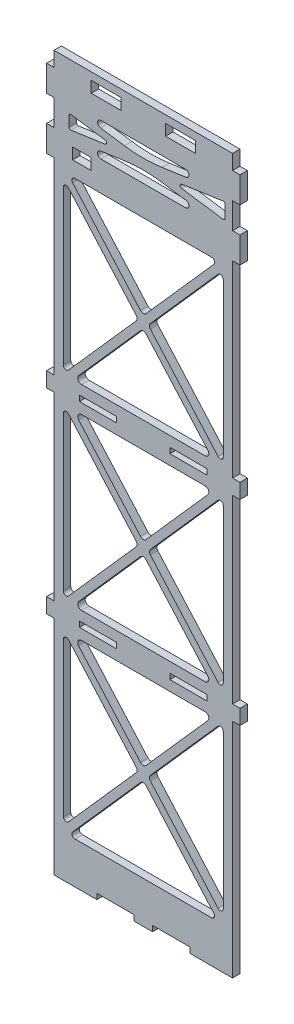
SolidWorks part; units mm, degrees
ref_plane "前视基准面" through (0, 0, 0) normal (0, 0, 1) x (1, 0, 0)
ref_plane "上视基准面" through (0, 0, 0) normal (0, 1, 0) x (1, 0, 0)
ref_plane "右视基准面" through (0, 0, 0) normal (1, 0, 0) x (0, 0, -1)
other "Configuration Table"
sketch "草图1" plane through (0, 0, 0) normal (0, 0, 1) x (1, 0, 0)
  line L0 (2550.9863, 1406.1084) -> (2502.9863, 1406.1084)
  line L1 (2500.9863, 1402.1084) -> (2500.9863, 1395.1084)
  line L2 (2500.9863, 1388.1084) -> (2500.9863, 1381.1084)
  line L3 (2500.9863, 1330.5084) -> (2500.9863, 1326.5084)
  line L4 (2500.9863, 1277.9084) -> (2500.9863, 1273.9084)
  line L5 (2550.9863, 1214.1084) -> (2539.4863, 1214.1084)
  line L6 (2529.4863, 1214.1084) -> (2524.4863, 1214.1084)
  line L7 (2514.4863, 1214.1084) -> (2502.9863, 1214.1084)
  line L8 (2552.9863, 1402.1084) -> (2552.9863, 1395.1084)
  line L9 (2552.9863, 1388.1084) -> (2552.9863, 1381.1084)
  line L10 (2502.9863, 1406.1084) -> (2502.9863, 1402.1084)
  line L11 (2502.9863, 1395.1084) -> (2502.9863, 1388.1084)
  line L12 (2500.9863, 1402.1084) -> (2502.9863, 1402.1084)
  line L13 (2500.9863, 1395.1084) -> (2502.9863, 1395.1084)
  line L14 (2500.9863, 1388.1084) -> (2502.9863, 1388.1084)
  line L15 (2500.9863, 1381.1084) -> (2502.9863, 1381.1084)
  line L16 (2500.9863, 1326.5084) -> (2502.9863, 1326.5084)
  line L17 (2502.9863, 1330.5084) -> (2500.9863, 1330.5084)
  line L18 (2502.9863, 1381.1084) -> (2502.9863, 1330.5084)
  line L19 (2500.9863, 1277.9084) -> (2502.9863, 1277.9084)
  line L20 (2502.9863, 1273.9084) -> (2500.9863, 1273.9084)
  line L21 (2502.9863, 1326.5084) -> (2502.9863, 1277.9084)
  line L22 (2502.9863, 1273.9084) -> (2502.9863, 1214.1084)
  line L23 (2550.9863, 1406.1084) -> (2550.9863, 1402.1084)
  line L24 (2550.9863, 1402.1084) -> (2552.9863, 1402.1084)
  line L25 (2552.9863, 1402.1084) -> (2552.9863, 1395.1084)
  line L26 (2552.9863, 1330.5084) -> (2552.9863, 1326.5084)
  line L27 (2552.9863, 1277.9084) -> (2552.9863, 1273.9084)
  line L28 (2550.9863, 1395.1084) -> (2550.9863, 1388.1084)
  line L29 (2552.9863, 1395.1084) -> (2550.9863, 1395.1084)
  line L30 (2552.9863, 1388.1084) -> (2550.9863, 1388.1084)
  line L31 (2552.9863, 1381.1084) -> (2550.9863, 1381.1084)
  line L32 (2552.9863, 1326.5084) -> (2550.9863, 1326.5084)
  line L33 (2550.9863, 1330.5084) -> (2552.9863, 1330.5084)
  line L34 (2550.9863, 1381.1084) -> (2550.9863, 1330.5084)
  line L35 (2552.9863, 1277.9084) -> (2550.9863, 1277.9084)
  line L36 (2550.9863, 1273.9084) -> (2552.9863, 1273.9084)
  line L37 (2550.9863, 1326.5084) -> (2550.9863, 1277.9084)
  line L38 (2550.9863, 1273.9084) -> (2550.9863, 1214.1084)
  line L39 (2508.5975, 1379.1084) -> (2526.9863, 1379.1084)
  line L40 (2507.9863, 1386.1084) -> (2512.9863, 1386.1084)
  line L41 (2507.9863, 1383.1084) -> (2512.9863, 1383.1084)
  line L42 (2545.375, 1379.1084) -> (2508.5975, 1379.1084)
  line L43 (2545.375, 1379.1084) -> (2538.8184, 1379.1084)
  line L44 (2515.1541, 1379.1084) -> (2508.5975, 1379.1084)
  line L45 (2508.8854, 1373.7575) -> (2525.0647, 1355.4711)
  line L46 (2527.7352, 1352.4528) -> (2544.3528, 1333.6711)
  line L47 (2507.9983, 1377.7783) -> (2523.2416, 1360.5499)
  line L48 (2528.9078, 1354.1458) -> (2545.0871, 1335.8594)
  line L49 (2545.0871, 1373.7575) -> (2528.9078, 1355.4711)
  line L50 (2526.2373, 1352.4528) -> (2509.6197, 1333.6711)
  line L51 (2545.9742, 1377.7783) -> (2530.7309, 1360.5499)
  line L52 (2525.0647, 1354.1458) -> (2508.8854, 1335.8594)
  line L53 (2523.2416, 1360.5499) -> (2524.0871, 1359.5942)
  line L54 (2530.7309, 1360.5499) -> (2529.8854, 1359.5942)
  line L55 (2524.0871, 1359.5942) -> (2526.2373, 1357.164)
  line L56 (2527.7352, 1357.164) -> (2529.8854, 1359.5942)
  line L57 (2548.4863, 1354.8084) -> (2548.4863, 1375.4878)
  line L58 (2545.0871, 1373.7575) -> (2547.0871, 1376.0179)
  line L59 (2548.4863, 1354.8084) -> (2548.4863, 1334.129)
  line L60 (2545.0871, 1335.8594) -> (2547.0871, 1333.5989)
  line L61 (2505.4863, 1354.8084) -> (2505.4863, 1375.4878)
  line L62 (2505.4863, 1354.8084) -> (2505.4863, 1334.129)
  line L63 (2508.8854, 1373.7575) -> (2506.8854, 1376.0179)
  line L64 (2508.8854, 1335.8594) -> (2506.8854, 1333.5989)
  line L65 (2519.8281, 1327.7584) -> (2519.8281, 1328.5084)
  line L66 (2519.8281, 1328.5084) -> (2519.8281, 1329.2584)
  line L67 (2509.8281, 1329.2584) -> (2509.8281, 1327.7584)
  line L68 (2519.8281, 1328.5084) -> (2519.8281, 1329.2584)
  line L69 (2519.8281, 1329.2584) -> (2509.8281, 1329.2584)
  line L70 (2519.8281, 1327.7584) -> (2509.8281, 1327.7584)
  line L71 (2534.1444, 1327.7584) -> (2534.1444, 1328.5084)
  line L72 (2534.1444, 1328.5084) -> (2534.1444, 1329.2584)
  line L73 (2544.1444, 1329.2584) -> (2544.1444, 1327.7584)
  line L74 (2534.1444, 1328.5084) -> (2534.1444, 1329.2584)
  line L75 (2534.1444, 1329.2584) -> (2544.1444, 1329.2584)
  line L76 (2534.1444, 1327.7584) -> (2544.1444, 1327.7584)
  line L77 (2519.8281, 1329.2584) -> (2519.8281, 1328.5084)
  line L78 (2508.8854, 1321.1575) -> (2525.0647, 1302.8711)
  line L79 (2527.7352, 1299.8528) -> (2544.3528, 1281.0711)
  line L80 (2509.6197, 1323.3458) -> (2523.2416, 1307.9499)
  line L81 (2528.9078, 1301.5458) -> (2545.0871, 1283.2594)
  line L82 (2545.0871, 1321.1575) -> (2528.9078, 1302.8711)
  line L83 (2526.2373, 1299.8528) -> (2509.6197, 1281.0711)
  line L84 (2544.3528, 1323.3458) -> (2530.7309, 1307.9499)
  line L85 (2525.0647, 1301.5458) -> (2508.8854, 1283.2594)
  line L86 (2523.2416, 1307.9499) -> (2524.0871, 1306.9942)
  line L87 (2530.7309, 1307.9499) -> (2529.8854, 1306.9942)
  line L88 (2524.0871, 1306.9942) -> (2526.2373, 1304.564)
  line L89 (2527.7352, 1304.564) -> (2529.8854, 1306.9942)
  line L90 (2548.4863, 1302.2084) -> (2548.4863, 1322.8878)
  line L91 (2545.0871, 1321.1575) -> (2547.0871, 1323.4179)
  line L92 (2548.4863, 1302.2084) -> (2548.4863, 1281.529)
  line L93 (2545.0871, 1283.2594) -> (2547.0871, 1280.9989)
  line L94 (2505.4863, 1302.2084) -> (2505.4863, 1322.8878)
  line L95 (2505.4863, 1302.2084) -> (2505.4863, 1281.529)
  line L96 (2508.8854, 1321.1575) -> (2506.8854, 1323.4179)
  line L97 (2508.8854, 1283.2594) -> (2506.8854, 1280.9989)
  line L98 (2519.8281, 1276.6584) -> (2519.8281, 1275.9084)
  line L99 (2519.8281, 1275.9084) -> (2519.8281, 1275.1584)
  line L100 (2509.8281, 1275.1584) -> (2509.8281, 1276.6584)
  line L101 (2519.8281, 1275.9084) -> (2519.8281, 1275.1584)
  line L102 (2519.8281, 1275.1584) -> (2509.8281, 1275.1584)
  line L103 (2519.8281, 1276.6584) -> (2509.8281, 1276.6584)
  line L104 (2534.1444, 1276.6584) -> (2534.1444, 1275.9084)
  line L105 (2534.1444, 1275.9084) -> (2534.1444, 1275.1584)
  line L106 (2544.1444, 1275.1584) -> (2544.1444, 1276.6584)
  line L107 (2534.1444, 1275.9084) -> (2534.1444, 1275.1584)
  line L108 (2534.1444, 1275.1584) -> (2544.1444, 1275.1584)
  line L109 (2534.1444, 1276.6584) -> (2544.1444, 1276.6584)
  line L110 (2519.8281, 1275.1584) -> (2519.8281, 1275.9084)
  line L111 (2526.9863, 1225.3084) -> (2508.5975, 1225.3084)
  line L112 (2526.9863, 1225.3084) -> (2545.375, 1225.3084)
  line L113 (2508.8854, 1268.5575) -> (2525.0647, 1250.2711)
  line L114 (2527.7352, 1247.2528) -> (2545.9742, 1226.6385)
  line L115 (2509.6197, 1270.7458) -> (2523.2416, 1255.3499)
  line L116 (2528.9078, 1248.9458) -> (2545.0871, 1230.6594)
  line L117 (2545.0871, 1268.5575) -> (2528.9078, 1250.2711)
  line L118 (2526.2373, 1247.2528) -> (2507.9983, 1226.6385)
  line L119 (2544.3528, 1270.7458) -> (2530.7309, 1255.3499)
  line L120 (2525.0647, 1248.9458) -> (2508.8854, 1230.6594)
  line L121 (2523.2416, 1255.3499) -> (2524.0871, 1254.3942)
  line L122 (2530.7309, 1255.3499) -> (2529.8854, 1254.3942)
  line L123 (2524.0871, 1254.3942) -> (2526.2373, 1251.964)
  line L124 (2527.7352, 1251.964) -> (2529.8854, 1254.3942)
  line L125 (2548.4863, 1249.6084) -> (2548.4863, 1270.2878)
  line L126 (2545.0871, 1268.5575) -> (2547.0871, 1270.8179)
  line L127 (2548.4863, 1249.6084) -> (2548.4863, 1228.929)
  line L128 (2545.0871, 1230.6594) -> (2547.0871, 1228.3989)
  line L129 (2505.4863, 1249.6084) -> (2505.4863, 1270.2878)
  line L130 (2505.4863, 1249.6084) -> (2505.4863, 1228.929)
  line L131 (2508.8854, 1268.5575) -> (2506.8854, 1270.8179)
  line L132 (2508.8854, 1230.6594) -> (2506.8854, 1228.3989)
  line L133 (2524.4863, 1214.1084) -> (2524.4863, 1214.8584)
  line L134 (2524.4863, 1214.8584) -> (2524.4863, 1215.6084)
  line L135 (2514.4863, 1215.6084) -> (2514.4863, 1214.1084)
  line L136 (2524.4863, 1214.8584) -> (2524.4863, 1215.6084)
  line L137 (2524.4863, 1215.6084) -> (2514.4863, 1215.6084)
  line L138 (2529.4863, 1214.1084) -> (2529.4863, 1214.8584)
  line L139 (2539.4863, 1215.6084) -> (2539.4863, 1214.1084)
  line L140 (2529.4863, 1215.6084) -> (2539.4863, 1215.6084)
  line L141 (2524.4863, 1215.6084) -> (2524.4863, 1214.8584)
  line L142 (2529.4863, 1215.6084) -> (2529.4863, 1214.8584)
  line L143 (2520.9863, 1404.1084) -> (2520.9863, 1401.1084)
  line L144 (2520.9863, 1404.1084) -> (2512.9863, 1404.1084)
  line L145 (2512.9863, 1404.1084) -> (2512.9863, 1401.1084)
  line L146 (2512.9863, 1401.1084) -> (2520.9863, 1401.1084)
  line L147 (2532.9863, 1404.1084) -> (2532.9863, 1401.1084)
  line L148 (2532.9863, 1404.1084) -> (2540.9863, 1404.1084)
  line L149 (2540.9863, 1404.1084) -> (2540.9863, 1401.1084)
  line L150 (2540.9863, 1401.1084) -> (2532.9863, 1401.1084)
  line L151 (2512.9863, 1386.1084) -> (2512.9863, 1383.1084)
  line L152 (2512.9863, 1383.1084) -> (2507.9863, 1383.1084)
  line L153 (2512.9863, 1383.1084) -> (2507.9863, 1383.1084)
  line L154 (2507.9863, 1383.1084) -> (2507.9863, 1386.1084)
  line L155 (2548.4151, 1393.7229) -> (2537.3079, 1392.1031)
  line L156 (2521.9355, 1389.8613) -> (2515.4822, 1388.9202)
  line L157 (2538.4913, 1394.2968) -> (2532.037, 1393.3556)
  line L158 (2516.6639, 1391.1137) -> (2507.5584, 1389.7858)
  line L159 (2548.4151, 1389.494) -> (2537.3079, 1391.1137)
  line L160 (2521.9355, 1393.3556) -> (2515.4822, 1394.2967)
  line L161 (2550.8433, 1387.1187) -> (2550.84, 1387.1192)
  line L162 (2538.4903, 1388.9202) -> (2532.037, 1389.8613)
  line L163 (2516.6639, 1392.1032) -> (2507.5584, 1393.4311)
  line L164 (2548.9863, 1393.228) -> (2548.9863, 1389.9889)
  line L165 (2515.6128, 1396.0977) -> (2538.3597, 1396.0977)
  line L166 (2515.6128, 1387.1192) -> (2538.3597, 1387.1192)
  line L167 (2506.9863, 1392.9363) -> (2506.9863, 1390.2805)
  line L168 (2526.9863, 1325.0084) -> (2510.3686, 1325.0084)
  line L169 (2526.9863, 1325.0084) -> (2543.6039, 1325.0084)
  line L170 (2526.9863, 1279.4084) -> (2510.3686, 1279.4084)
  line L171 (2526.9863, 1279.4084) -> (2543.6039, 1279.4084)
  line L172 (2526.9863, 1272.4084) -> (2510.3686, 1272.4084)
  line L173 (2526.9863, 1272.4084) -> (2543.6039, 1272.4084)
  line L174 (2526.9863, 1332.0084) -> (2510.3686, 1332.0084)
  line L175 (2526.9863, 1332.0084) -> (2543.6039, 1332.0084)
  arc A0 (2508.5975, 1379.1084) -> (2507.9983, 1377.7783) centre (2508.5975, 1378.3084) ccw
  arc A1 (2525.0647, 1354.1458) -> (2525.0647, 1355.4711) centre (2524.3158, 1354.8084) ccw
  arc A2 (2526.2373, 1357.164) -> (2527.7352, 1357.164) centre (2526.9863, 1357.8266) ccw
  arc A3 (2528.9078, 1355.4711) -> (2528.9078, 1354.1458) centre (2529.6567, 1354.8084) ccw
  arc A4 (2545.9742, 1377.7783) -> (2545.375, 1379.1084) centre (2545.375, 1378.3084) ccw
  arc A5 (2527.7352, 1352.4528) -> (2526.2373, 1352.4528) centre (2526.9863, 1351.7902) ccw
  arc A6 (2548.4863, 1375.4878) -> (2547.0871, 1376.0179) centre (2547.6863, 1375.4878) ccw
  arc A7 (2547.0871, 1333.5989) -> (2548.4863, 1334.129) centre (2547.6863, 1334.129) ccw
  arc A8 (2506.8854, 1376.0179) -> (2505.4863, 1375.4878) centre (2506.2863, 1375.4878) ccw
  arc A9 (2505.4863, 1334.129) -> (2506.8854, 1333.5989) centre (2506.2863, 1334.129) ccw
  arc A10 (2525.0647, 1301.5458) -> (2525.0647, 1302.8711) centre (2524.3158, 1302.2084) ccw
  arc A11 (2526.2373, 1304.564) -> (2527.7352, 1304.564) centre (2526.9863, 1305.2266) ccw
  arc A12 (2528.9078, 1302.8711) -> (2528.9078, 1301.5458) centre (2529.6567, 1302.2084) ccw
  arc A13 (2527.7352, 1299.8528) -> (2526.2373, 1299.8528) centre (2526.9863, 1299.1902) ccw
  arc A14 (2548.4863, 1322.8878) -> (2547.0871, 1323.4179) centre (2547.6863, 1322.8878) ccw
  arc A15 (2547.0871, 1280.9989) -> (2548.4863, 1281.529) centre (2547.6863, 1281.529) ccw
  arc A16 (2506.8854, 1323.4179) -> (2505.4863, 1322.8878) centre (2506.2863, 1322.8878) ccw
  arc A17 (2505.4863, 1281.529) -> (2506.8854, 1280.9989) centre (2506.2863, 1281.529) ccw
  arc A18 (2525.0647, 1248.9458) -> (2525.0647, 1250.2711) centre (2524.3158, 1249.6084) ccw
  arc A19 (2526.2373, 1251.964) -> (2527.7352, 1251.964) centre (2526.9863, 1252.6266) ccw
  arc A20 (2528.9078, 1250.2711) -> (2528.9078, 1248.9458) centre (2529.6567, 1249.6084) ccw
  arc A21 (2507.9983, 1226.6385) -> (2508.5975, 1225.3084) centre (2508.5975, 1226.1084) ccw
  arc A22 (2545.375, 1225.3084) -> (2545.9742, 1226.6385) centre (2545.375, 1226.1084) ccw
  arc A23 (2527.7352, 1247.2528) -> (2526.2373, 1247.2528) centre (2526.9863, 1246.5902) ccw
  arc A24 (2548.4863, 1270.2878) -> (2547.0871, 1270.8179) centre (2547.6863, 1270.2878) ccw
  arc A25 (2547.0871, 1228.3989) -> (2548.4863, 1228.929) centre (2547.6863, 1228.929) ccw
  arc A26 (2506.8854, 1270.8179) -> (2505.4863, 1270.2878) centre (2506.2863, 1270.2878) ccw
  arc A27 (2505.4863, 1228.929) -> (2506.8854, 1228.3989) centre (2506.2863, 1228.929) ccw
  arc A28 (2516.6639, 1391.1137) -> (2516.6639, 1392.1032) centre (2516.5918, 1391.6084) ccw
  arc A29 (2532.037, 1389.8613) -> (2521.9355, 1389.8613) centre (2526.9863, 1355.2276) ccw
  arc A30 (2507.5584, 1393.4311) -> (2506.9863, 1392.9363) centre (2507.4863, 1392.9363) ccw
  arc A31 (2537.3079, 1392.1031) -> (2537.3086, 1391.1137) centre (2537.3808, 1391.6084) ccw
  arc A32 (2521.9355, 1393.3556) -> (2532.037, 1393.3556) centre (2526.9863, 1427.9892) ccw
  arc A33 (2548.4151, 1389.494) -> (2548.9863, 1389.9889) centre (2548.4863, 1389.9889) ccw
  arc A34 (2548.9863, 1393.228) -> (2548.4151, 1393.7229) centre (2548.4863, 1393.228) ccw
  arc A35 (2515.6128, 1396.0977) -> (2515.4822, 1394.2967) centre (2515.6128, 1395.1924) ccw
  arc A36 (2515.4822, 1388.9202) -> (2515.6128, 1387.1192) centre (2515.6128, 1388.0244) ccw
  arc A37 (2538.4913, 1394.2968) -> (2538.3597, 1396.0977) centre (2538.3597, 1395.1924) ccw
  arc A38 (2538.3597, 1387.1192) -> (2538.4903, 1388.9202) centre (2538.3597, 1388.0244) ccw
  arc A39 (2506.9863, 1390.2805) -> (2507.5584, 1389.7858) centre (2507.4863, 1390.2805) ccw
  arc A40 (2510.3686, 1325.0084) -> (2509.6197, 1323.3458) centre (2510.3686, 1324.0084) ccw
  arc A41 (2544.3528, 1323.3458) -> (2543.6039, 1325.0084) centre (2543.6039, 1324.0084) ccw
  arc A42 (2509.6197, 1281.0711) -> (2510.3686, 1279.4084) centre (2510.3686, 1280.4084) ccw
  arc A43 (2543.6039, 1279.4084) -> (2544.3528, 1281.0711) centre (2543.6039, 1280.4084) ccw
  arc A44 (2510.3686, 1272.4084) -> (2509.6197, 1270.7458) centre (2510.3686, 1271.4084) ccw
  arc A45 (2544.3528, 1270.7458) -> (2543.6039, 1272.4084) centre (2543.6039, 1271.4084) ccw
  arc A46 (2509.6197, 1333.6711) -> (2510.3686, 1332.0084) centre (2510.3686, 1333.0084) ccw
  arc A47 (2543.6039, 1332.0084) -> (2544.3528, 1333.6711) centre (2543.6039, 1333.0084) ccw
extrude "凸台-拉伸1" add sketch "草图1" along normal blind 2
